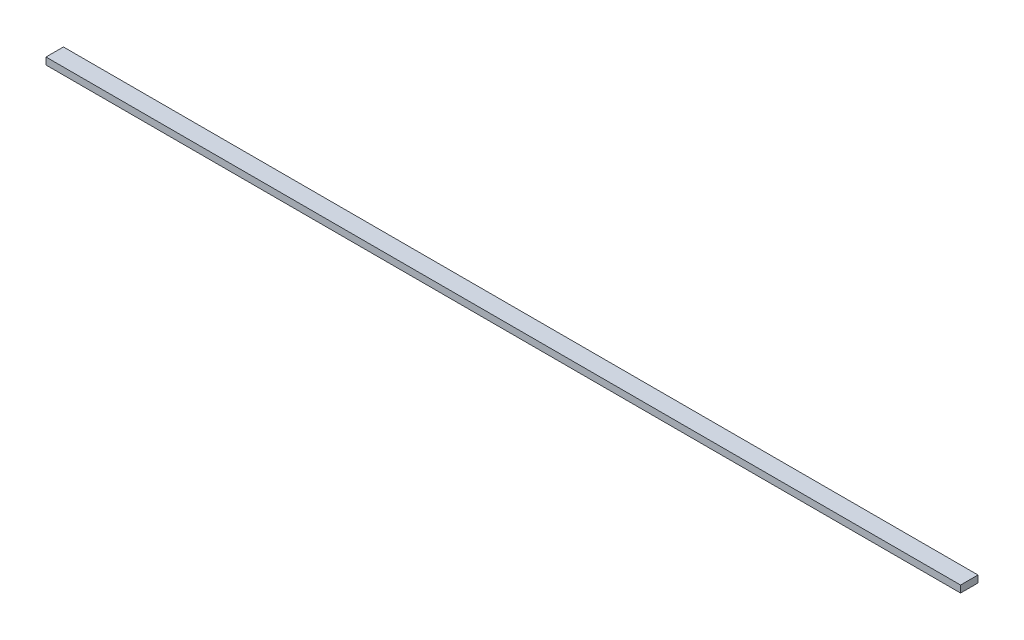
SolidWorks part; units mm, degrees
ref_plane "Alzado" through (0, 0, 0) normal (0, 0, 1) x (1, 0, 0)
ref_plane "Planta" through (0, 0, 0) normal (0, 1, 0) x (1, 0, 0)
ref_plane "Vista lateral" through (0, 0, 0) normal (1, 0, 0) x (0, 0, -1)
sketch "Croquis2" plane through (0, 0, 0) normal (1, 0, 0) x (0, 0, -1)
  line L1 (0, 0) -> (200, 0)
  line L2 (0, 0) -> (0, -80)
  line L3 (0, -80) -> (200, -80)
  line L4 (200, 0) -> (200, -80)
  dimension "D1" = 200
  dimension "D2" = 80
extrude "Saliente-Extruir1" add sketch "Croquis2" along normal blind 10500
